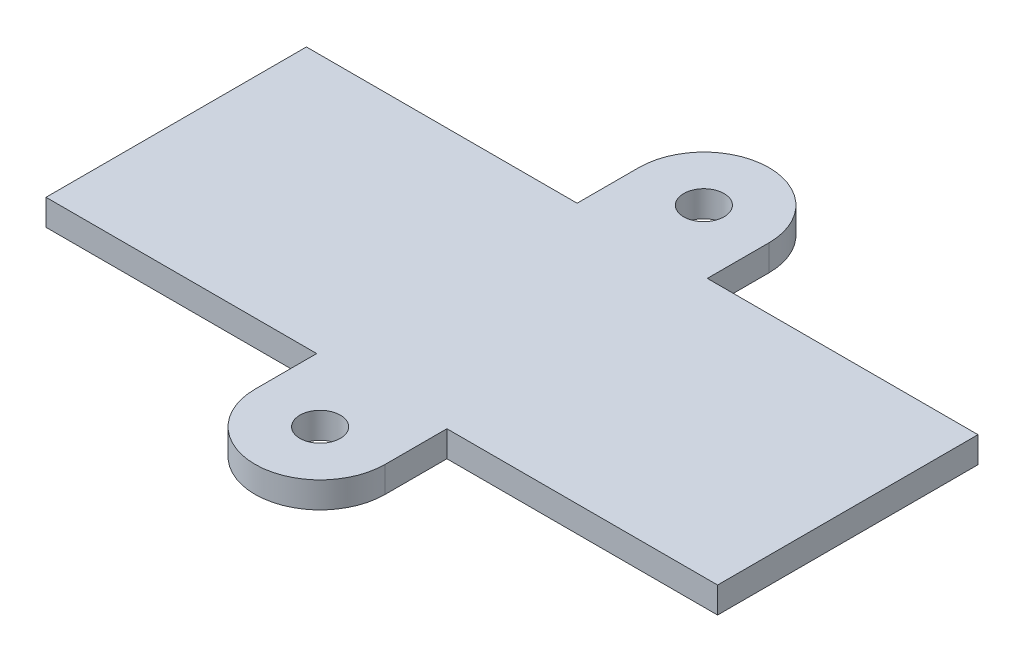
SolidWorks part; units mm, degrees
ref_plane "Front Plane" through (0, 0, 0) normal (0, 0, 1) x (1, 0, 0)
ref_plane "Top Plane" through (0, 0, 0) normal (0, 1, 0) x (1, 0, 0)
ref_plane "Right Plane" through (0, 0, 0) normal (1, 0, 0) x (0, 0, -1)
sketch "Sketch1" plane through (0, 0, 0) normal (0, 1, 0) x (1, 0, 0)
  line L1 (-24.5, 9.5) -> (24.5, 9.5)
  line L2 (-24.5, 9.5) -> (-24.5, -9.5)
  line L3 (-24.5, -9.5) -> (24.5, -9.5)
  line L4 (24.5, 9.5) -> (24.5, -9.5)
  line L5 (-24.5, 9.5) -> (24.5, -9.5) construction
  line L6 (-24.5, -9.5) -> (24.5, 9.5) construction
  point P0 (0, 0)
  dimension "D1" = 49
  dimension "D2" = 19
extrude "Boss-Extrude1" add sketch "Sketch1" along normal blind 1.9
sketch "Sketch2" plane through (0, 0, 0) normal (0, 1, 0) x (1, 0, 0)
  line L0 (0, 9.5) -> (0, -9.5) construction
  line L1 (24.5, 9.5) -> (-24.5, 9.5) construction
  line L2 (-24.5, -9.5) -> (24.5, -9.5) construction
  line L3 (-24.5, 0) -> (24.5, 0) construction
  line L4 (-24.5, 9.5) -> (-24.5, -9.5) construction
  line L5 (24.5, -9.5) -> (24.5, 9.5) construction
  line L6 (-4.75, 14) -> (-4.75, 9.5)
  line L7 (4.75, 14) -> (4.75, 9.5)
  line L8 (4.75, 9.5) -> (-4.75, 9.5)
  line L9 (4.75, -14) -> (4.75, -9.5)
  line L10 (4.75, -9.5) -> (-4.75, -9.5)
  line L11 (-4.75, -14) -> (-4.75, -9.5)
  arc A0 (-4.75, 14) -> (4.75, 14) centre (0, 14) cw
  circle A1 centre (0, 14) radius 1.4732
  circle A2 centre (0, -14) radius 1.4732
  arc A3 (-4.75, -14) -> (4.75, -14) centre (0, -14) ccw
  dimension "D1" = 9.5
  dimension "D3" = 2.9464
  dimension "D2" = 4.5
extrude "Boss-Extrude2" add sketch "Sketch2" along normal blind 1.9
